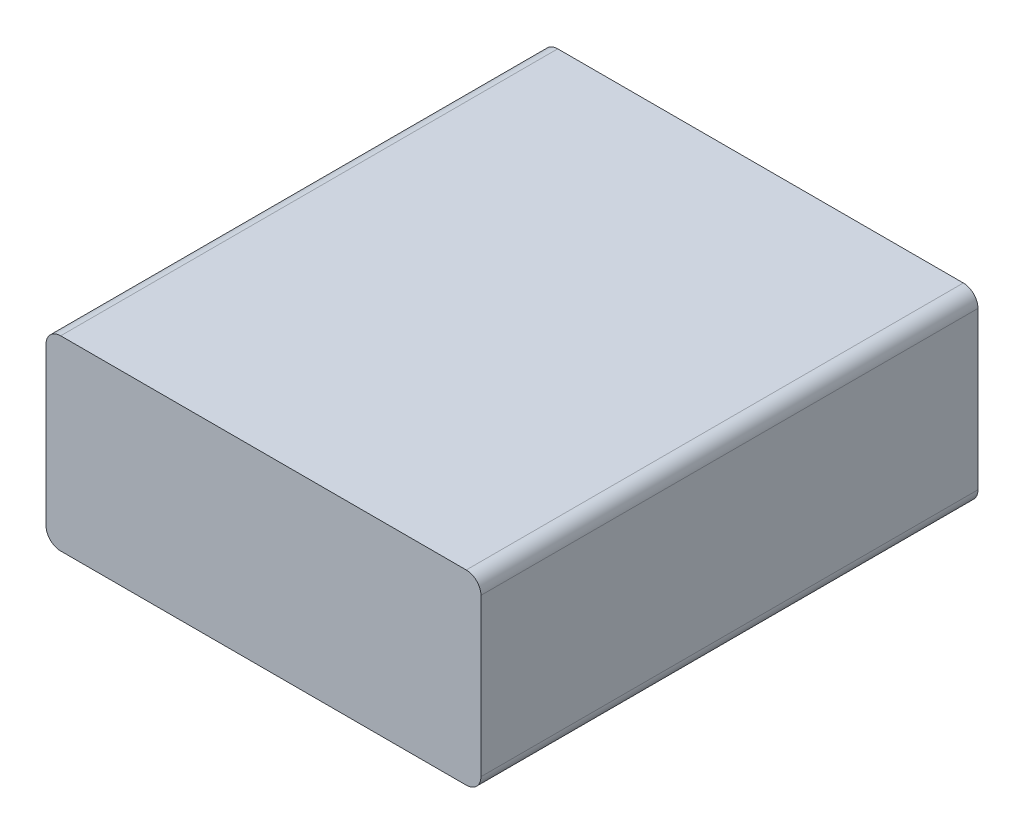
SolidWorks part; units mm, degrees
ref_plane "Front Plane" through (0, 0, 0) normal (0, 0, 1) x (1, 0, 0)
ref_plane "Top Plane" through (0, 0, 0) normal (0, 1, 0) x (1, 0, 0)
ref_plane "Right Plane" through (0, 0, 0) normal (1, 0, 0) x (0, 0, -1)
sketch "Sketch1" plane through (0, 0, 0) normal (0, 0, 1) x (1, 0, 0)
  line L1 (41.45, -19.05) -> (-41.45, -19.05)
  line L2 (44.45, -16.05) -> (44.45, 16.05)
  line L3 (41.45, 19.05) -> (-41.45, 19.05)
  line L4 (-44.45, -16.05) -> (-44.45, 16.05)
  line L5 (44.45, -19.05) -> (-44.45, 19.05) construction
  line L6 (44.45, 19.05) -> (-44.45, -19.05) construction
  arc A0 (-41.45, -19.05) -> (-44.45, -16.05) centre (-41.45, -16.05) cw
  arc A1 (-41.45, 19.05) -> (-44.45, 16.05) centre (-41.45, 16.05) ccw
  arc A2 (44.45, 16.05) -> (41.45, 19.05) centre (41.45, 16.05) ccw
  arc A3 (41.45, -19.05) -> (44.45, -16.05) centre (41.45, -16.05) ccw
  point P0 (0, 0)
  dimension "D3" = 3
  dimension "D1" = 88.9
  dimension "D2" = 38.1
extrude "Boss-Extrude1" add sketch "Sketch1" along normal blind 101.6
equation "\"ChainSeperation\"= 80"
